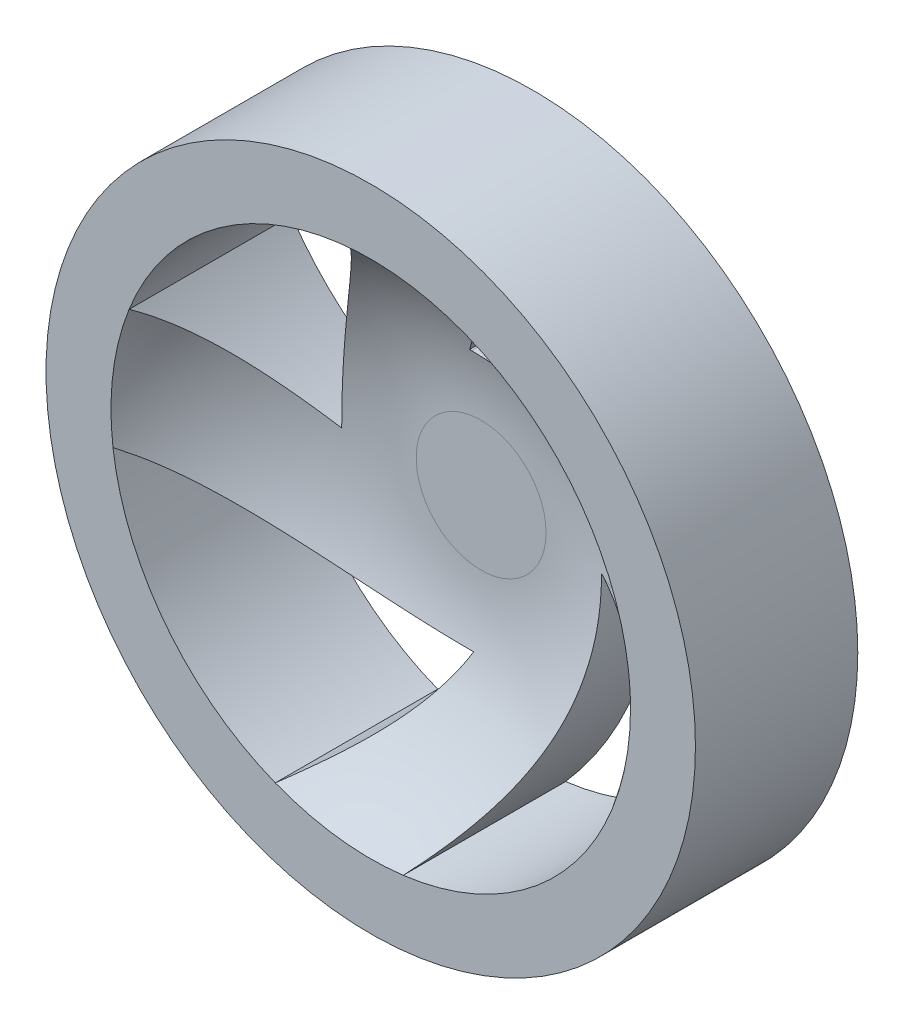
SolidWorks part; units mm, degrees
ref_plane "Front Plane" through (0, 0, 0) normal (0, 0, 1) x (1, 0, 0)
ref_plane "Top Plane" through (0, 0, 0) normal (0, 1, 0) x (1, 0, 0)
ref_plane "Right Plane" through (0, 0, 0) normal (1, 0, 0) x (0, 0, -1)
sketch "Sketch1" plane through (0, 0, 0) normal (0, 0, 1) x (1, 0, 0)
  circle A0 centre (0, 0) radius 50
  arc A1 (0, -20) -> (0.3125, -19.9976) centre (0, 0) ccw
  arc A2 (-39.6863, -5) -> (-14.6875, -37.2059) centre (0, 0) ccw
  arc A3 (-5, 39.6863) -> (-20, 0) centre (40, 0) ccw
  arc A5 (39.6863, 5) -> (0, 20) centre (0, -40) ccw
  arc A6 (5, -39.6863) -> (20, 0) centre (-40, 0) ccw
  arc A7 (-39.6863, -5) -> (0, -20) centre (0, 40) ccw
  arc A8 (37.2059, -14.6875) -> (19.9976, 0.3125) centre (0, -40) ccw
  arc A9 (14.6875, 37.2059) -> (-0.3125, 19.9976) centre (40, 0) ccw
  arc A10 (-37.2059, 14.6875) -> (-19.9976, -0.3125) centre (0, 40) ccw
  arc A11 (-14.6875, -37.2059) -> (0.3125, -19.9976) centre (-40, 0) ccw
  arc A12 (6.25, 29.7647) -> (-5, 0) centre (40, 0) ccw construction
  arc A13 (29.7647, -6.25) -> (0, 5) centre (0, -40) ccw construction
  arc A14 (-6.25, -29.7647) -> (5, 0) centre (-40, 0) ccw construction
  arc A15 (-29.7647, 6.25) -> (0, -5) centre (0, 40) ccw construction
  arc A16 (-20, 0) -> (-19.9976, -0.3125) centre (0, 0) ccw
  arc A17 (-5, 39.6863) -> (-37.2059, 14.6875) centre (0, 0) ccw
  arc A18 (0, 20) -> (-0.3125, 19.9976) centre (0, 0) ccw
  arc A19 (39.6863, 5) -> (14.6875, 37.2059) centre (0, 0) ccw
  arc A20 (20, 0) -> (19.9976, 0.3125) centre (0, 0) ccw
  arc A21 (5, -39.6863) -> (37.2059, -14.6875) centre (0, 0) ccw
  point P29 (14.6551, 37.1838)
  point P31 (14.7009, 37.2006)
  point P32 (-5, 0)
  point P33 (37.1829, -14.7455)
  point P35 (-14.3601, -36.981)
  point P37 (-37.2109, 14.6748)
  point P39 (-14.6548, -37.2188)
  dimension "D1" = 100
  dimension "D2" = 40
  dimension "D3" = 10
  dimension "D4" = 60
  dimension "D5" = 15
extrude "Boss-Extrude1" add sketch "Sketch1" along normal blind 25
sketch "Sketch3" plane through (0, 0, 0) normal (1, 0, 0) x (0, 0, -1)
  line L0 (-25, 0) -> (0, 0) construction
  line L1 (-25, 50) -> (-25, -50) construction
  line L2 (-25, 40) -> (-25, -40)
  line L3 (-8, 10) -> (-8, -10)
  line L4 (0, -50) -> (0, 50) construction
  arc A0 (-25, 40) -> (-8, 10) centre (-43, 9.9833) cw
  arc A1 (-25, -40) -> (-8, -10) centre (-43, -9.9833) ccw
  point P7 (-25, 0)
  point P10 (-8, 0)
  point P14 (-8, 9.4833)
  dimension "D3" = 35
  dimension "D1" = 80
  dimension "D2" = 8
  dimension "D4" = 20
revolve "Cut-Revolve4" cut sketch "Sketch3" angle 360 about L0
